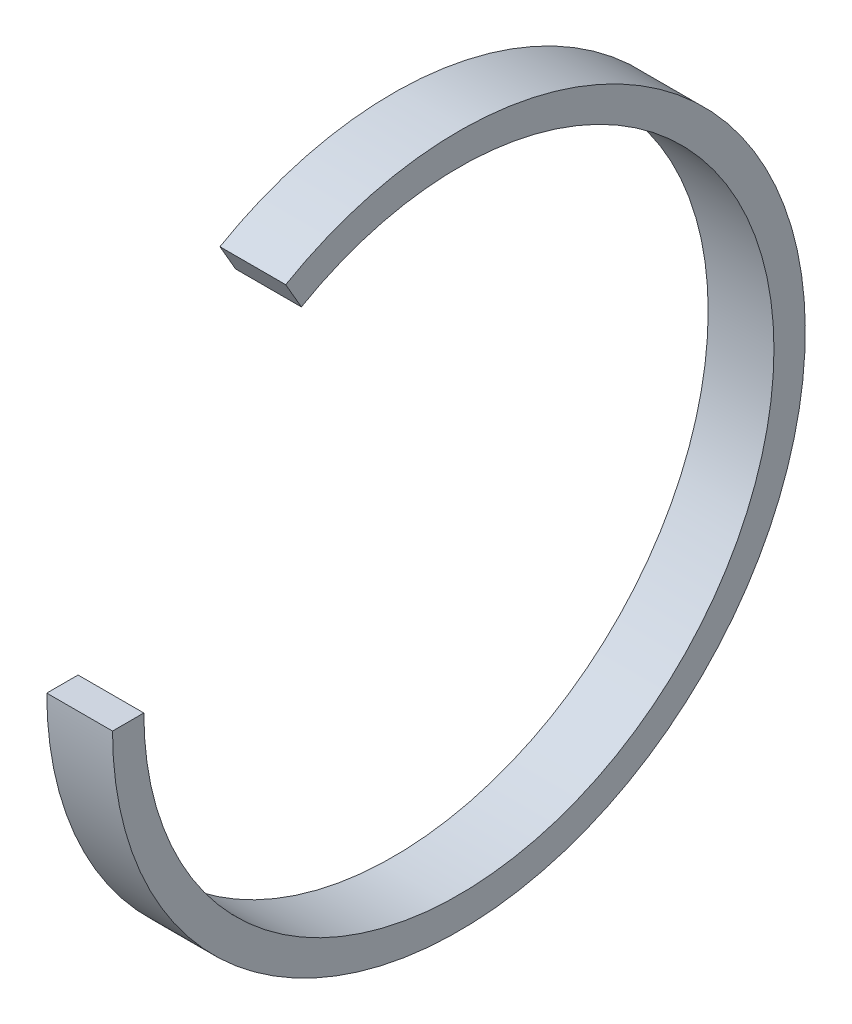
SolidWorks part; units mm, degrees
ref_plane "Front Plane" through (0, 0, 0) normal (0, 0, 1) x (1, 0, 0)
ref_plane "Top Plane" through (0, 0, 0) normal (0, 1, 0) x (1, 0, 0)
ref_plane "Right Plane" through (0, 0, 0) normal (1, 0, 0) x (0, 0, -1)
ref_plane "Plane1" through (0, 0, 0) normal (-1, 0, 0) x (0, -1, 0)
sketch "Sketch1" plane through (0, 0, 0) normal (-1, 0, 0) x (0, -1, 0)
  line L0 (-43.5611, 25.15) -> (-47.8912, 27.65)
  line L1 (0, 55.3) -> (0, 50.3)
  arc A0 (0, 50.3) -> (-43.5611, 25.15) centre (0, 0) cw
  arc A1 (-47.8912, 27.65) -> (0, 55.3) centre (0, 0) ccw
extrude "Boss-Extrude1" add sketch "Sketch1" against normal blind 10.5
